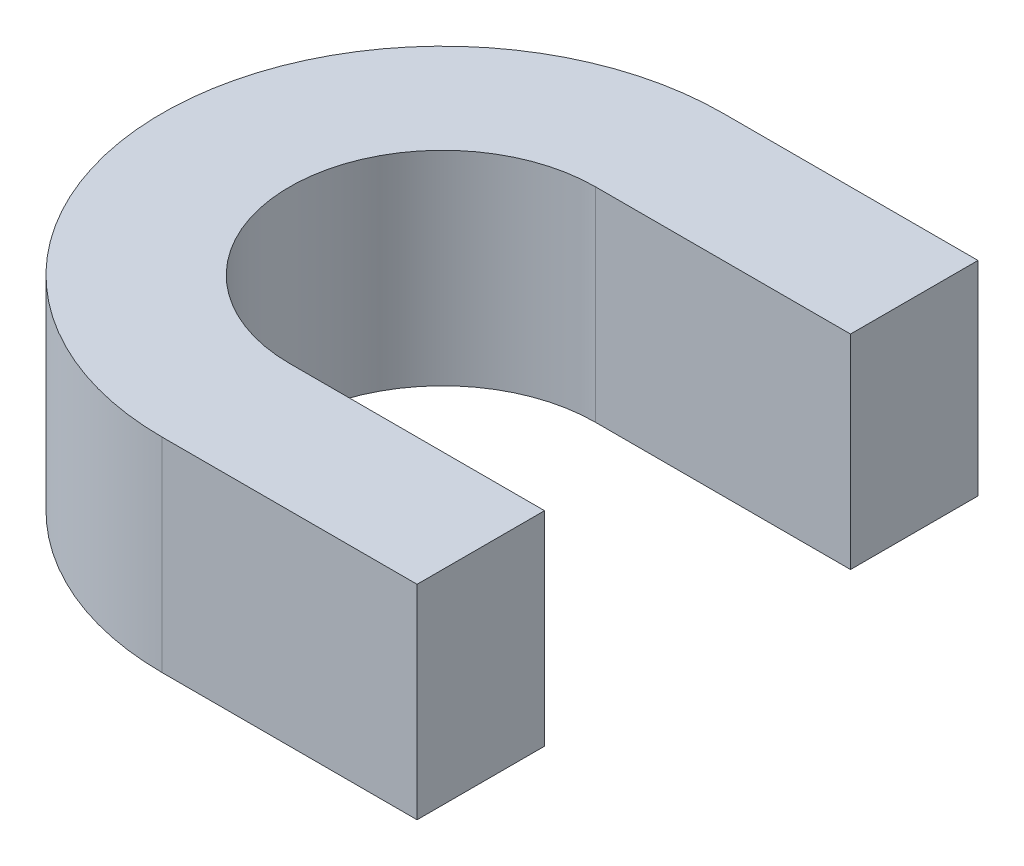
SolidWorks part; units mm, degrees
ref_plane "Front Plane" through (0, 0, 0) normal (0, 0, 1) x (1, 0, 0)
ref_plane "Top Plane" through (0, 0, 0) normal (0, 1, 0) x (1, 0, 0)
ref_plane "Right Plane" through (0, 0, 0) normal (1, 0, 0) x (0, 0, -1)
sketch "Sketch1" plane through (0, 0, 0) normal (0, 1, 0) x (1, 0, 0)
  line L0 (0, 11) -> (10, 11)
  line L1 (10, 11) -> (10, 6)
  line L2 (10, 6) -> (0, 6)
  line L4 (0, -6) -> (10, -6)
  line L5 (10, -6) -> (10, -11)
  line L6 (10, -11) -> (0, -11)
  arc A0 (0, 6) -> (0, -6) centre (0, 0) ccw
  arc A1 (0, 11) -> (0, -11) centre (0, 0) ccw
  dimension "D1" = 12
  dimension "D2" = 5
  dimension "D3" = 10
extrude "Boss-Extrude1" add sketch "Sketch1" along normal blind 8
